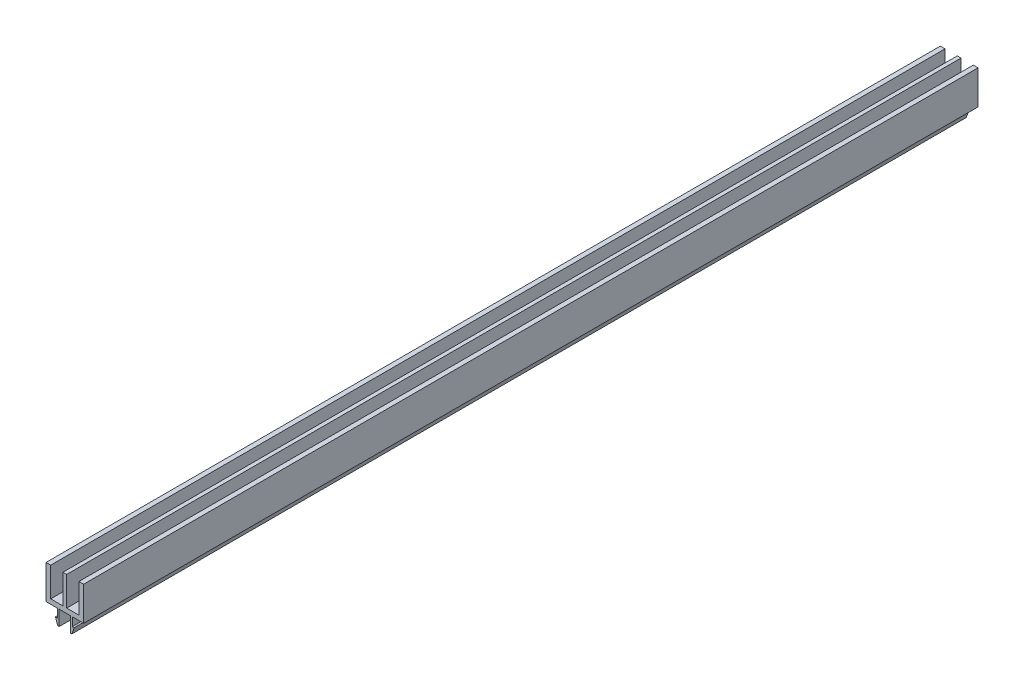
SolidWorks part; units mm, degrees
ref_plane "Plan de face" through (0, 0, 0) normal (0, 0, 1) x (1, 0, 0)
ref_plane "Plan de dessus" through (0, 0, 0) normal (0, 1, 0) x (1, 0, 0)
ref_plane "Plan de droite" through (0, 0, 0) normal (1, 0, 0) x (0, 0, -1)
ref_plane "Plan1" through (0, 0, 50) normal (0, 0, 1) x (1, 0, 0)
sketch "Esquisse1" plane through (0, 0, 50) normal (0, 0, 1) x (1, 0, 0)
  line L0 (-1, 2.5) -> (-7.5, 2.5)
  line L1 (-7.5, 2.5) -> (-7.5, 18)
  line L2 (-7.5, 18) -> (-10, 18)
  line L3 (-10, 18) -> (-10, 0)
  line L4 (-10, 0) -> (-4, 0)
  line L5 (-4, 0) -> (-4, -4.5)
  line L6 (-4, -4.5) -> (-5, -4.5)
  line L7 (-5, -4.5) -> (-3.75, -8)
  line L8 (-3.75, -8) -> (-3, -8)
  line L9 (-3, -8) -> (-3, 0)
  line L10 (-3, 0) -> (3, 0)
  line L11 (3, 0) -> (3, -8)
  line L12 (3, -8) -> (3.75, -8)
  line L13 (3.75, -8) -> (5, -4.5)
  line L14 (5, -4.5) -> (4, -4.5)
  line L15 (4, -4.5) -> (4, 0)
  line L16 (4, 0) -> (10, 0)
  line L17 (10, 0) -> (10, 18)
  line L18 (10, 18) -> (7.5, 18)
  line L19 (7.5, 18) -> (7.5, 2.5)
  line L20 (7.5, 2.5) -> (1, 2.5)
  line L21 (1, 2.5) -> (1, 18)
  line L22 (1, 18) -> (-1, 18)
  line L23 (-1, 18) -> (-1, 2.5)
extrude "Boss.-Extru.1" add sketch "Esquisse1" against normal blind 475
